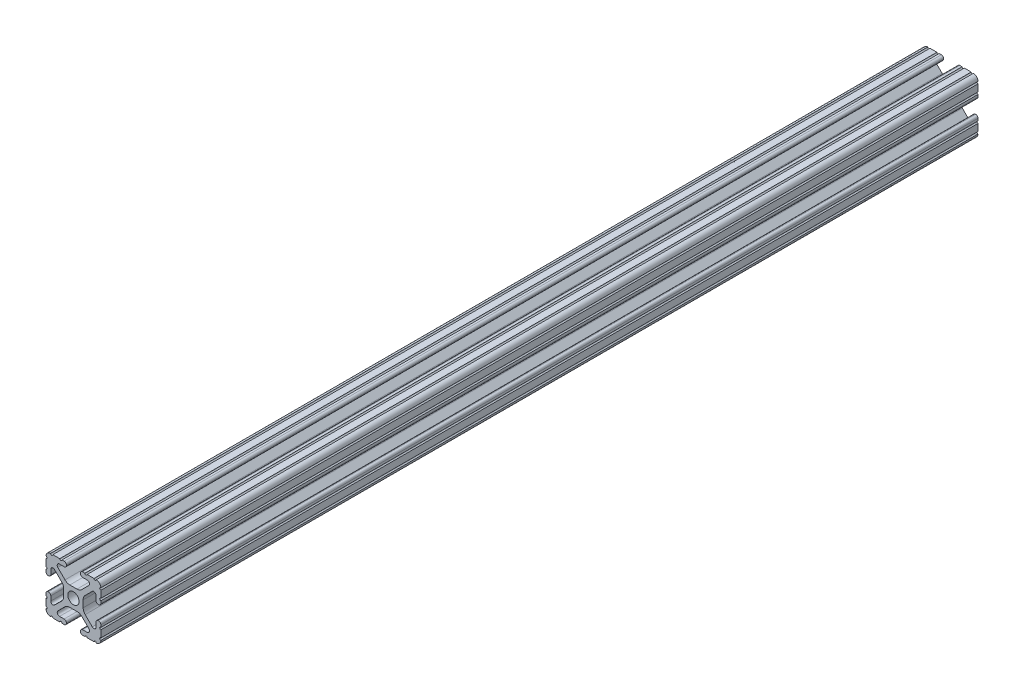
SolidWorks part; units mm, degrees
material "6061 Alloy"
ref_plane "Front Plane" through (0, 0, 0) normal (0, 0, 1) x (1, 0, 0)
ref_plane "Top Plane" through (0, 0, 0) normal (0, 1, 0) x (1, 0, 0)
ref_plane "Right Plane" through (0, 0, 0) normal (1, 0, 0) x (0, 0, -1)
sketch "Sketch1" plane through (0, 0, 0) normal (0, 0, 1) x (1, 0, 0)
  line L88 (-7.1797, -8.6452) -> (-3.9523, -5.4237)
  line L89 (-1.7093, -4.4958) -> (1.7093, -4.4958)
  line L90 (3.9523, -5.4237) -> (7.1797, -8.6452)
  line L91 (6.4164, -10.4902) -> (4.2875, -10.4902)
  line L92 (3.2385, -11.5392) -> (3.2385, -11.651)
  line L93 (4.2875, -12.7) -> (5.3171, -12.7)
  line L94 (6.3331, -12.7) -> (9.5504, -12.7)
  line L95 (12.7, -9.5504) -> (12.7, -6.3331)
  line L96 (12.7, -5.3171) -> (12.7, -4.2875)
  line L97 (11.651, -3.2385) -> (11.5392, -3.2385)
  line L98 (10.4902, -4.2875) -> (10.4902, -6.4021)
  line L99 (8.7371, -7.1294) -> (5.441, -3.8408)
  line L100 (4.5085, -1.5932) -> (4.5085, 1.5932)
  line L101 (5.441, 3.8408) -> (8.7371, 7.1294)
  line L102 (10.4902, 6.4021) -> (10.4902, 4.2875)
  line L103 (11.5392, 3.2385) -> (11.651, 3.2385)
  line L104 (12.7, 4.2875) -> (12.7, 5.3171)
  line L105 (12.7, 6.3331) -> (12.7, 9.5504)
  line L106 (9.5504, 12.7) -> (6.3331, 12.7)
  line L107 (5.3171, 12.7) -> (4.2875, 12.7)
  line L108 (3.2385, 11.651) -> (3.2385, 11.5392)
  line L109 (4.2875, 10.4902) -> (6.4768, 10.4902)
  line L110 (7.207, 8.7244) -> (3.8983, 5.4232)
  line L111 (1.6558, 4.4958) -> (-1.6558, 4.4958)
  line L112 (-3.8983, 5.4232) -> (-7.207, 8.7244)
  line L113 (-6.4768, 10.4902) -> (-4.2875, 10.4902)
  line L114 (-3.2385, 11.5392) -> (-3.2385, 11.651)
  line L115 (-4.2875, 12.7) -> (-5.3171, 12.7)
  line L116 (-6.3331, 12.7) -> (-9.5504, 12.7)
  line L117 (-12.7, 9.5504) -> (-12.7, 6.3331)
  line L118 (-12.7, 5.3171) -> (-12.7, 4.2875)
  line L119 (-11.651, 3.2385) -> (-11.5392, 3.2385)
  line L120 (-10.4902, 4.2875) -> (-10.4902, 6.4021)
  line L121 (-8.7371, 7.1294) -> (-5.441, 3.8408)
  line L122 (-4.5085, 1.5932) -> (-4.5085, -1.5932)
  line L123 (-5.441, -3.8408) -> (-8.7371, -7.1294)
  line L124 (-10.4902, -6.4021) -> (-10.4902, -4.2875)
  line L125 (-11.5392, -3.2385) -> (-11.651, -3.2385)
  line L126 (-12.7, -4.2875) -> (-12.7, -5.3171)
  line L127 (-12.7, -6.3331) -> (-12.7, -9.5504)
  line L128 (-9.5504, -12.7) -> (-6.3331, -12.7)
  line L129 (-5.3171, -12.7) -> (-4.2875, -12.7)
  line L130 (-3.2385, -11.651) -> (-3.2385, -11.5392)
  line L131 (-4.2875, -10.4902) -> (-6.4164, -10.4902)
  circle A1 centre (0, 0) radius 2.6035
  arc A104 (-7.1797, -8.6452) -> (-6.4164, -10.4902) centre (-6.4164, -9.4098) ccw
  arc A105 (-1.7093, -4.4958) -> (-3.9523, -5.4237) centre (-1.7093, -7.6708) ccw
  arc A106 (3.9523, -5.4237) -> (1.7093, -4.4958) centre (1.7093, -7.6708) ccw
  arc A107 (6.4164, -10.4902) -> (7.1797, -8.6452) centre (6.4164, -9.4098) ccw
  arc A108 (4.2875, -10.4902) -> (3.2385, -11.5392) centre (4.2875, -11.5392) ccw
  arc A109 (3.2385, -11.651) -> (4.2875, -12.7) centre (4.2875, -11.651) ccw
  arc A110 (6.3331, -12.7) -> (5.3171, -12.7) centre (5.8251, -12.7) ccw
  arc A111 (10.5664, -12.6998) -> (9.5504, -12.7) centre (10.0584, -12.7) ccw
  arc A112 (10.5664, -12.6998) -> (12.6998, -10.5664) centre (10.5918, -10.5918) ccw
  arc A113 (12.7, -9.5504) -> (12.6998, -10.5664) centre (12.7, -10.0584) ccw
  arc A114 (12.7, -5.3171) -> (12.7, -6.3331) centre (12.7, -5.8251) ccw
  arc A115 (12.7, -4.2875) -> (11.651, -3.2385) centre (11.651, -4.2875) ccw
  arc A116 (11.5392, -3.2385) -> (10.4902, -4.2875) centre (11.5392, -4.2875) ccw
  arc A117 (8.7371, -7.1294) -> (10.4902, -6.4021) centre (9.4628, -6.4021) ccw
  arc A118 (4.5085, -1.5932) -> (5.441, -3.8408) centre (7.6835, -1.5932) ccw
  arc A119 (5.441, 3.8408) -> (4.5085, 1.5932) centre (7.6835, 1.5932) ccw
  arc A120 (10.4902, 6.4021) -> (8.7371, 7.1294) centre (9.4628, 6.4021) ccw
  arc A121 (10.4902, 4.2875) -> (11.5392, 3.2385) centre (11.5392, 4.2875) ccw
  arc A122 (11.651, 3.2385) -> (12.7, 4.2875) centre (11.651, 4.2875) ccw
  arc A123 (12.7, 6.3331) -> (12.7, 5.3171) centre (12.7, 5.8251) ccw
  arc A124 (12.6998, 10.5664) -> (12.7, 9.5504) centre (12.7, 10.0584) ccw
  arc A125 (12.6998, 10.5664) -> (10.5664, 12.6998) centre (10.5918, 10.5918) ccw
  arc A126 (9.5504, 12.7) -> (10.5664, 12.6998) centre (10.0584, 12.7) ccw
  arc A127 (5.3171, 12.7) -> (6.3331, 12.7) centre (5.8251, 12.7) ccw
  arc A128 (4.2875, 12.7) -> (3.2385, 11.651) centre (4.2875, 11.651) ccw
  arc A129 (3.2385, 11.5392) -> (4.2875, 10.4902) centre (4.2875, 11.5392) ccw
  arc A130 (7.207, 8.7244) -> (6.4768, 10.4902) centre (6.4768, 9.4563) ccw
  arc A131 (1.6558, 4.4958) -> (3.8983, 5.4232) centre (1.6558, 7.6708) ccw
  arc A132 (-3.8983, 5.4232) -> (-1.6558, 4.4958) centre (-1.6558, 7.6708) ccw
  arc A133 (-6.4768, 10.4902) -> (-7.207, 8.7244) centre (-6.4768, 9.4563) ccw
  arc A134 (-4.2875, 10.4902) -> (-3.2385, 11.5392) centre (-4.2875, 11.5392) ccw
  arc A135 (-3.2385, 11.651) -> (-4.2875, 12.7) centre (-4.2875, 11.651) ccw
  arc A136 (-6.3331, 12.7) -> (-5.3171, 12.7) centre (-5.8251, 12.7) ccw
  arc A137 (-10.5664, 12.6998) -> (-9.5504, 12.7) centre (-10.0584, 12.7) ccw
  arc A138 (-10.5664, 12.6998) -> (-12.6998, 10.5664) centre (-10.5918, 10.5918) ccw
  arc A139 (-12.7, 9.5504) -> (-12.6998, 10.5664) centre (-12.7, 10.0584) ccw
  arc A140 (-12.7, 5.3171) -> (-12.7, 6.3331) centre (-12.7, 5.8251) ccw
  arc A141 (-12.7, 4.2875) -> (-11.651, 3.2385) centre (-11.651, 4.2875) ccw
  arc A142 (-11.5392, 3.2385) -> (-10.4902, 4.2875) centre (-11.5392, 4.2875) ccw
  arc A143 (-8.7371, 7.1294) -> (-10.4902, 6.4021) centre (-9.4628, 6.4021) ccw
  arc A144 (-4.5085, 1.5932) -> (-5.441, 3.8408) centre (-7.6835, 1.5932) ccw
  arc A145 (-5.441, -3.8408) -> (-4.5085, -1.5932) centre (-7.6835, -1.5932) ccw
  arc A146 (-10.4902, -6.4021) -> (-8.7371, -7.1294) centre (-9.4628, -6.4021) ccw
  arc A147 (-10.4902, -4.2875) -> (-11.5392, -3.2385) centre (-11.5392, -4.2875) ccw
  arc A148 (-11.651, -3.2385) -> (-12.7, -4.2875) centre (-11.651, -4.2875) ccw
  arc A149 (-12.7, -6.3331) -> (-12.7, -5.3171) centre (-12.7, -5.8251) ccw
  arc A150 (-12.6998, -10.5664) -> (-12.7, -9.5504) centre (-12.7, -10.0584) ccw
  arc A151 (-12.6998, -10.5664) -> (-10.5664, -12.6998) centre (-10.5918, -10.5918) ccw
  arc A152 (-9.5504, -12.7) -> (-10.5664, -12.6998) centre (-10.0584, -12.7) ccw
  arc A153 (-5.3171, -12.7) -> (-6.3331, -12.7) centre (-5.8251, -12.7) ccw
  arc A154 (-4.2875, -12.7) -> (-3.2385, -11.651) centre (-4.2875, -11.651) ccw
  arc A155 (-3.2385, -11.5392) -> (-4.2875, -10.4902) centre (-4.2875, -11.5392) ccw
extrude "Boss-Extrude1" add sketch "Sketch1" along normal mid plane 406.4
equation "\"deep\"= 6in"
equation "\"high\"= 20.5in"
equation "\"wide\"= 14in"
equation "\"Length@Boss-Extrude1\"      = \"front wide\""
equation "\"front wide\"= 16in"
